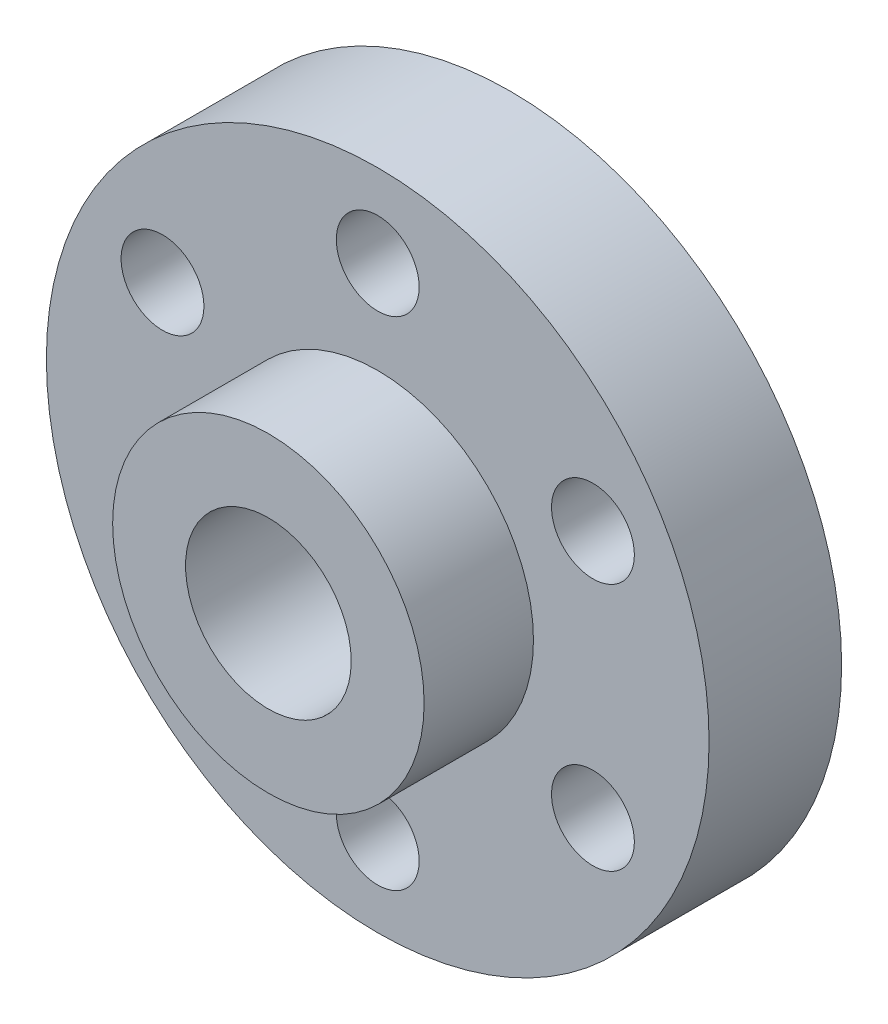
SolidWorks part; units mm, degrees
ref_plane "Front Plane" through (0, 0, 0) normal (0, 0, 1) x (1, 0, 0)
ref_plane "Top Plane" through (0, 0, 0) normal (0, 1, 0) x (1, 0, 0)
ref_plane "Right Plane" through (0, 0, 0) normal (1, 0, 0) x (0, 0, -1)
sketch "Sketch1" plane through (0, 0, 0) normal (0, 0, 1) x (1, 0, 0)
  circle A0 centre (0, 0) radius 12.7
  circle A1 centre (0, 0) radius 9.525 construction
  circle A2 centre (0, 9.525) radius 1.5875
  circle A3 centre (8.2489, 4.7625) radius 1.5875
  circle A4 centre (8.2489, -4.7625) radius 1.5875
  circle A5 centre (0, -9.525) radius 1.5875
  circle A6 centre (-8.2489, -4.7625) radius 1.5875
  circle A7 centre (-8.2489, 4.7625) radius 1.5875
  point P7 (8.3082, -11.6028)
  point P8 (0, 0)
  point P18 (0, 0)
  dimension "D1" = 25.4
  dimension "D2" = 19.05
  dimension "D3" = 3.175
  dimension "D4" = 6
extrude "Boss-Extrude1" add sketch "Sketch1" along normal blind 5.08
sketch "Sketch2" plane through (0, 0, 5.08) normal (0, 0, 1) x (1, 0, 0)
  circle A0 centre (0, 0) radius 5.969
  dimension "D1" = 11.938
extrude "Boss-Extrude2" add sketch "Sketch2" along normal blind 4.191
sketch "Sketch3" plane through (0, 0, 9.271) normal (0, 0, 1) x (1, 0, 0)
  circle A0 centre (0, 0) radius 3.175
  dimension "D1" = 6.35
extrude "Cut-Extrude1" cut sketch "Sketch3" against normal up to surface (9.271 mm away) up to face at (12.7, 0, 0)
